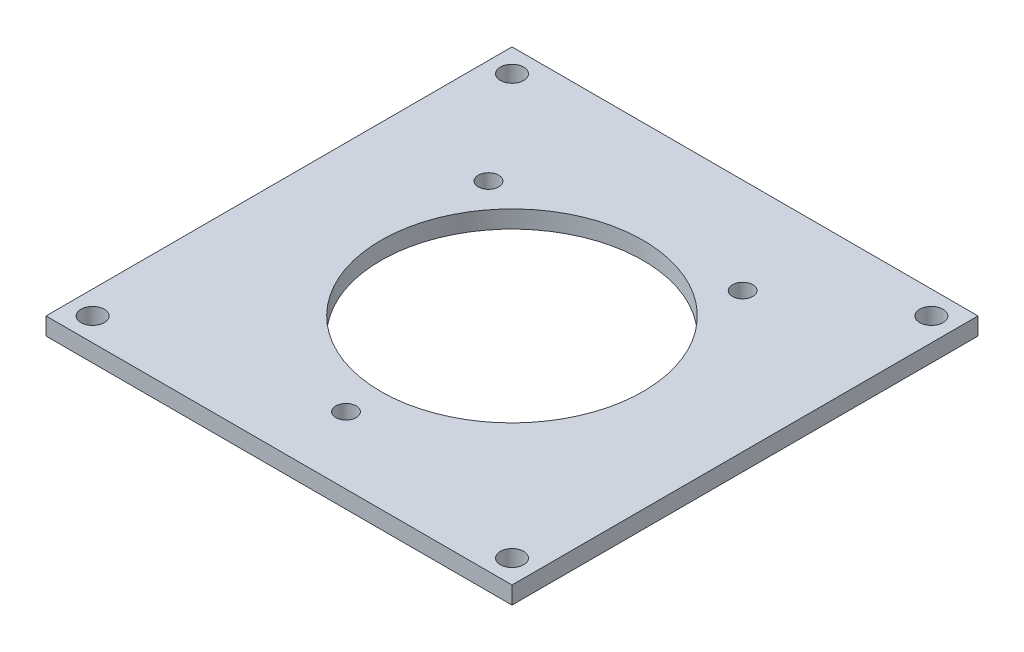
SolidWorks part; units mm, degrees
ref_plane "Plan de face" through (0, 0, 0) normal (0, 0, 1) x (1, 0, 0)
ref_plane "Plan de dessus" through (0, 0, 0) normal (0, 1, 0) x (1, 0, 0)
ref_plane "Plan de droite" through (0, 0, 0) normal (1, 0, 0) x (0, 0, -1)
sketch "Esquisse1" plane through (0, 0, 0) normal (0, 1, 0) x (1, 0, 0)
  line L0 (0, 0) -> (0, 40) construction
  line L1 (-40, 40) -> (40, 40)
  line L2 (-40, 40) -> (-40, -40)
  line L3 (-40, -40) -> (40, -40)
  line L4 (40, 40) -> (40, -40)
  line L5 (0, 0) -> (40, 0) construction
  line L6 (0, 0) -> (0, -28.5) construction
  line L7 (0, 0) -> (-22.0713, 18.0307) construction
  line L8 (0, 0) -> (16.0288, 23.5654) construction
  circle A0 centre (-36, 36) radius 2
  circle A1 centre (-22.0713, 18.0307) radius 1.75
  circle A2 centre (0, -28.5) radius 1.75
  circle A3 centre (16.0288, 23.5654) radius 1.75
  circle A4 centre (36, 36) radius 2
  circle A5 centre (-36, -36) radius 2
  circle A6 centre (36, -36) radius 2
  circle A7 centre (0, 0) radius 22.5
  dimension "D4" = 3.5
  dimension "D5" = 4
  dimension "D8" = 45
  dimension "D1" = 80
  dimension "D2" = 28.5
  dimension "D3" = 38.5
  dimension "D6" = 4
  dimension "D7" = 4
  dimension "D9" = 51.5
extrude "Extrusion1" add sketch "Esquisse1" along normal blind 3
